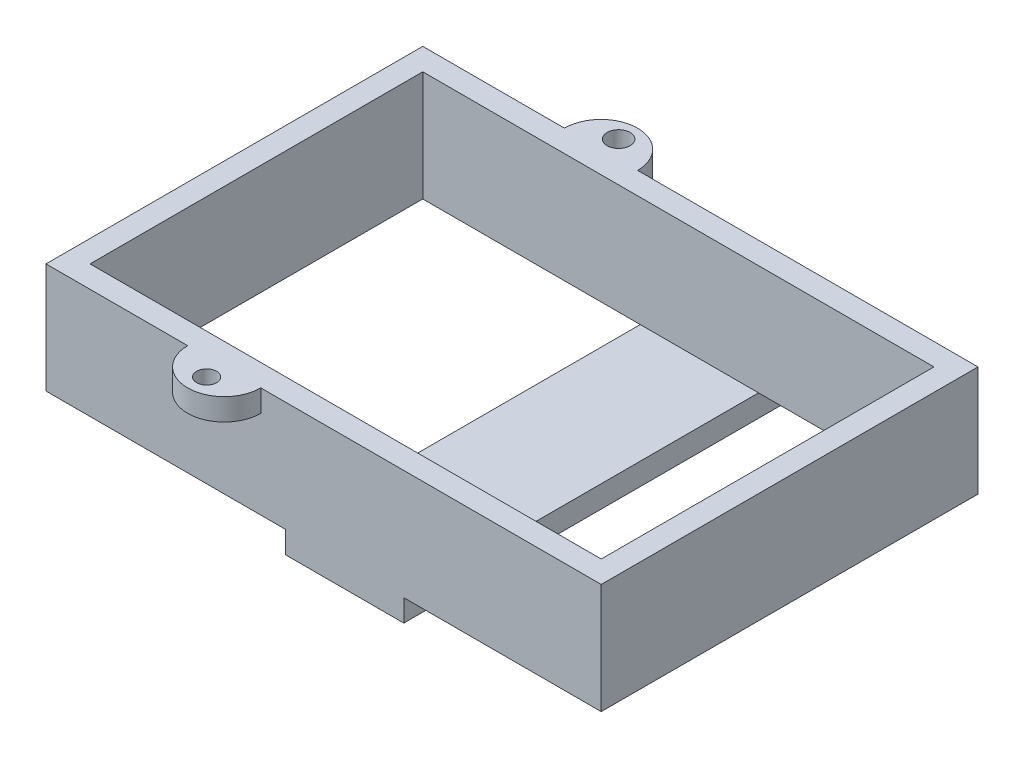
SolidWorks part; units mm, degrees
ref_plane "Front Plane" through (0, 0, 0) normal (0, 0, 1) x (1, 0, 0)
ref_plane "Top Plane" through (0, 0, 0) normal (0, 1, 0) x (1, 0, 0)
ref_plane "Right Plane" through (0, 0, 0) normal (1, 0, 0) x (0, 0, -1)
sketch "Sketch1" plane through (0, 0, 0) normal (0, 1, 0) x (1, 0, 0)
  line L0 (-34.5888, 21.5004) -> (29.4192, 21.5004)
  line L1 (-32.0488, 18.9604) -> (26.8792, 18.9604)
  line L2 (-32.0488, 18.9604) -> (-32.0488, -19.3936)
  line L3 (-32.0488, -19.3936) -> (26.8792, -19.3936)
  line L4 (26.8792, 18.9604) -> (26.8792, -19.3936)
  line L5 (29.4192, 21.5004) -> (29.4192, -21.9336)
  line L6 (-34.5888, -21.9336) -> (29.4192, -21.9336)
  line L7 (-34.5888, 21.5004) -> (-34.5888, -21.9336)
  dimension "D1" = 38.354
  dimension "D2" = 58.928
  dimension "D3" = 2.54
extrude "Boss-Extrude1" add sketch "Sketch1" against normal blind 12.7
sketch "Sketch2" plane through (0, -12.7, 0) normal (0, -1, 0) x (1, 0, 0)
  line L1 (6.6608, 21.9336) -> (-6.9775, 21.9336)
  line L2 (6.6608, 21.9336) -> (6.6608, -21.5004)
  line L3 (6.6608, -21.5004) -> (-6.9775, -21.5004)
  line L4 (-6.9775, 21.9336) -> (-6.9775, -21.5004)
extrude "Boss-Extrude2" add sketch "Sketch2" along normal blind 2.54
sketch "Sketch3" plane through (0, 0, 0) normal (0, 1, 0) x (1, 0, 0)
  line L4 (-9.8238, 30.0959) -> (-9.8238, -37.6724) construction
  line L5 (-32.0488, 18.9604) -> (-32.0488, -19.3936) construction
  line L6 (29.4192, 21.5004) -> (-34.5888, 21.5004) construction
  line L7 (-34.5888, -21.9336) -> (29.4192, -21.9336) construction
  arc A0 (-18.2559, 21.5004) -> (-9.8238, 21.5004) centre (-14.0399, 21.5004) cw
  arc A1 (-9.8238, -21.9336) -> (-18.2559, -21.9336) centre (-14.0399, -21.9336) cw
  circle A2 centre (-14.0399, 23.5324) radius 1.328
  circle A3 centre (-14.0399, -23.9656) radius 1.1467
  line M6 (-34.5888, -21.9336) -> (29.4192, -21.9336)
  line M8 (29.4192, 21.5004) -> (-34.5888, 21.5004)
  dimension "D1" = 22.225
  dimension "D2" = 47.498
  dimension "D3" = 2.032
extrude "Boss-Extrude3" add sketch "Sketch3" against normal blind 2.54 contours A0 A2 M8 | A1 A3 M6
